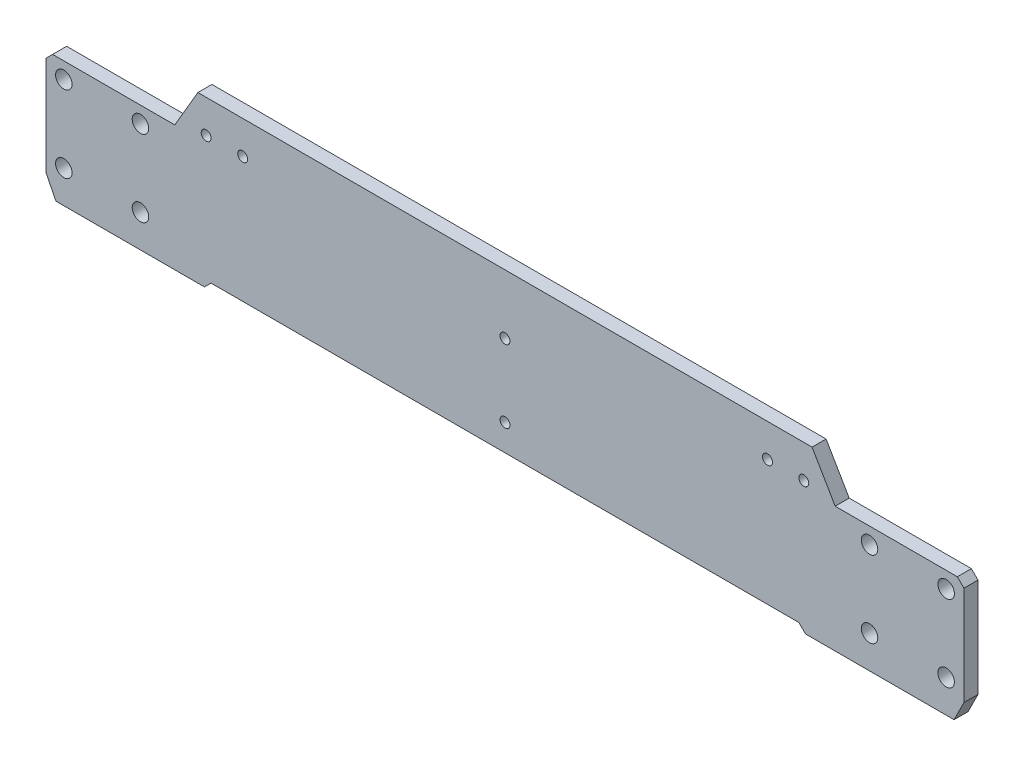
SolidWorks part; units mm, degrees
material "6063-O, Extruded Rod (SS)"
ref_plane "Front Plane" through (0, 0, 0) normal (0, 0, 1) x (1, 0, 0)
ref_plane "Top Plane" through (0, 0, 0) normal (0, 1, 0) x (1, 0, 0)
ref_plane "Right Plane" through (0, 0, 0) normal (1, 0, 0) x (0, 0, -1)
sketch "Sketch1" plane through (0, 0, 0) normal (0, 0, 1) x (1, 0, 0)
  line L0 (-89, -1) -> (89, -1)
  line L1 (89, -1) -> (91, -3)
  line L2 (91, -3) -> (136, -3)
  line L3 (136, -3) -> (139, 3)
  line L4 (139, 3) -> (139, 33)
  line L5 (139, 33) -> (137, 35)
  line L6 (137, 35) -> (100, 35)
  line L7 (100, 35) -> (93, 47)
  line L8 (93, 47) -> (-93, 47)
  line L9 (-93, 47) -> (-100, 35)
  line L10 (-100, 35) -> (-137, 35)
  line L11 (-137, 35) -> (-139, 33)
  line L12 (-139, 33) -> (-139, 3)
  line L13 (-139, 3) -> (-136, -3)
  line L14 (-136, -3) -> (-91, -3)
  line L15 (-91, -3) -> (-89, -1)
  circle A0 centre (-133.6003, 30.0998) radius 2.5
  circle A1 centre (-110.3972, 30.0866) radius 2.5
  circle A2 centre (-133.598, 6.8858) radius 2.5006
  circle A3 centre (-110.4, 6.9) radius 2.5
  circle A4 centre (-90.5, 37) radius 1.5
  circle A5 centre (-79.435, 37.0054) radius 1.5
  circle A6 centre (0, 29) radius 1.5
  circle A7 centre (0.0075, 6.9932) radius 1.5
  circle A8 centre (79.5, 37) radius 1.5
  circle A9 centre (90.5, 37) radius 1.5
  circle A10 centre (110.4, 30.1) radius 2.5
  circle A11 centre (133.5998, 30.1) radius 2.5002
  circle A12 centre (110.4, 6.8999) radius 2.5
  circle A13 centre (133.5999, 6.8998) radius 2.5002
extrude "Boss-Extrude1" add sketch "Sketch1" along normal blind 4.25
